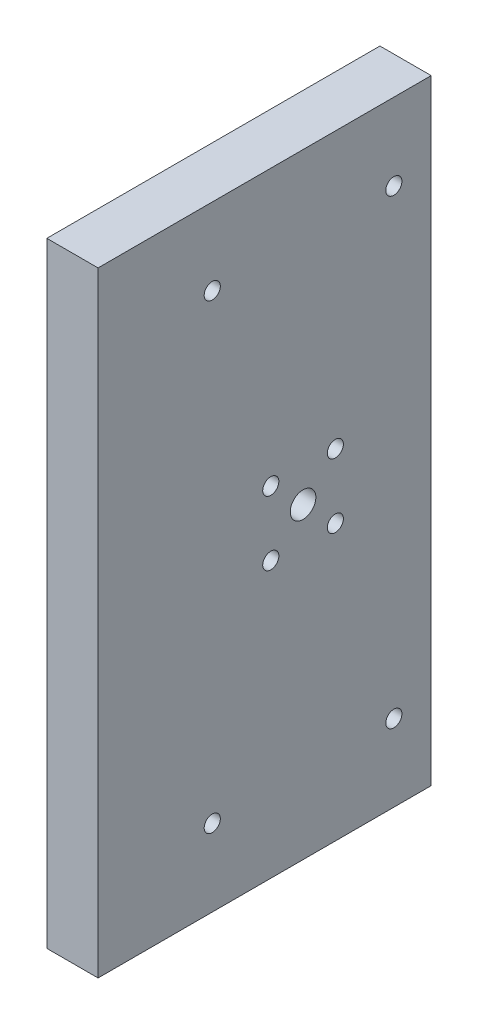
SolidWorks part; units mm, degrees
ref_plane "Plan de face" through (0, 0, 0) normal (0, 0, 1) x (1, 0, 0)
ref_plane "Plan de dessus" through (0, 0, 0) normal (0, 1, 0) x (1, 0, 0)
ref_plane "Plan de droite" through (0, 0, 0) normal (1, 0, 0) x (0, 0, -1)
sketch "Esquisse1" plane through (0, 0, 0) normal (1, 0, 0) x (0, 0, -1)
  line L1 (-41.275, 76.2) -> (41.275, 76.2)
  line L2 (-41.275, 76.2) -> (-41.275, -76.2)
  line L3 (-41.275, -76.2) -> (41.275, -76.2)
  line L4 (41.275, 76.2) -> (41.275, -76.2)
  line L5 (-41.275, 76.2) -> (41.275, -76.2) construction
  line L6 (-41.275, -76.2) -> (41.275, 76.2) construction
  point P0 (0, 0)
  dimension "D1" = 82.55
  dimension "D2" = 152.4
extrude "Boss.-Extru.1" add sketch "Esquisse1" along normal blind 12.7
sketch "Esquisse2" plane through (12.7, 0, 0) normal (1, 0, 0) x (0, 0, -1)
  line L0 (-41.275, 76.2) -> (-41.275, -76.2) construction
  line L1 (32.025, -57.15) -> (-12.975, -57.15) construction
  line L2 (32.025, -57.15) -> (32.025, 57.15) construction
  line L3 (32.025, 57.15) -> (-12.975, 57.15) construction
  line L4 (-12.975, -57.15) -> (-12.975, 57.15) construction
  line L5 (41.275, 76.2) -> (-41.275, 76.2) construction
  circle A0 centre (-12.975, 57.15) radius 2
  circle A1 centre (32.025, 57.15) radius 2
  circle A2 centre (-12.975, -57.15) radius 2
  circle A3 centre (32.025, -57.15) radius 2
  point P0 (0, 0)
  dimension "D3" = 4
  dimension "D1" = 45
  dimension "D2" = 114.3
  dimension "D4" = 28.3
  dimension "D5" = 19.05
extrude "Enlèv. mat.-Extru.1" cut sketch "Esquisse2" against normal through all
sketch "Esquisse3" plane through (12.7, 0, 0) normal (1, 0, 0) x (0, 0, -1)
  line L0 (-41.275, 76.2) -> (-41.275, -76.2) construction
  line L1 (1.525, -8) -> (17.525, -8) construction
  line L2 (1.525, -8) -> (1.525, 8) construction
  line L3 (1.525, 8) -> (17.525, 8) construction
  line L4 (17.525, -8) -> (17.525, 8) construction
  line L5 (1.525, -8) -> (17.525, 8) construction
  line L6 (1.525, 8) -> (17.525, -8) construction
  line L7 (41.275, 76.2) -> (-41.275, 76.2) construction
  circle A0 centre (9.525, 0) radius 3.175
  circle A1 centre (17.525, 8) radius 2
  circle A2 centre (1.525, 8) radius 2
  circle A3 centre (1.525, -8) radius 2
  circle A4 centre (17.525, -8) radius 2
  dimension "D1" = 6.35
  dimension "D4" = 4
  dimension "D2" = 16
  dimension "D3" = 16
  dimension "D5" = 50.8
  dimension "D6" = 76.2
extrude "Enlèv. mat.-Extru.2" cut sketch "Esquisse3" against normal through all
sketch "Esquisse4" plane through (0, 0, 0) normal (1, 0, 0) x (0, 0, -1)
  circle A0 centre (17.525, 8) radius 4.7625
  circle A1 centre (1.525, 8) radius 4.7625
  circle A2 centre (1.525, -8) radius 4.7625
  circle A3 centre (17.525, -8) radius 4.7625
  dimension "D1" = 9.525
extrude "Enlèv. mat.-Extru.3" cut sketch "Esquisse4" along normal blind 4.7625
